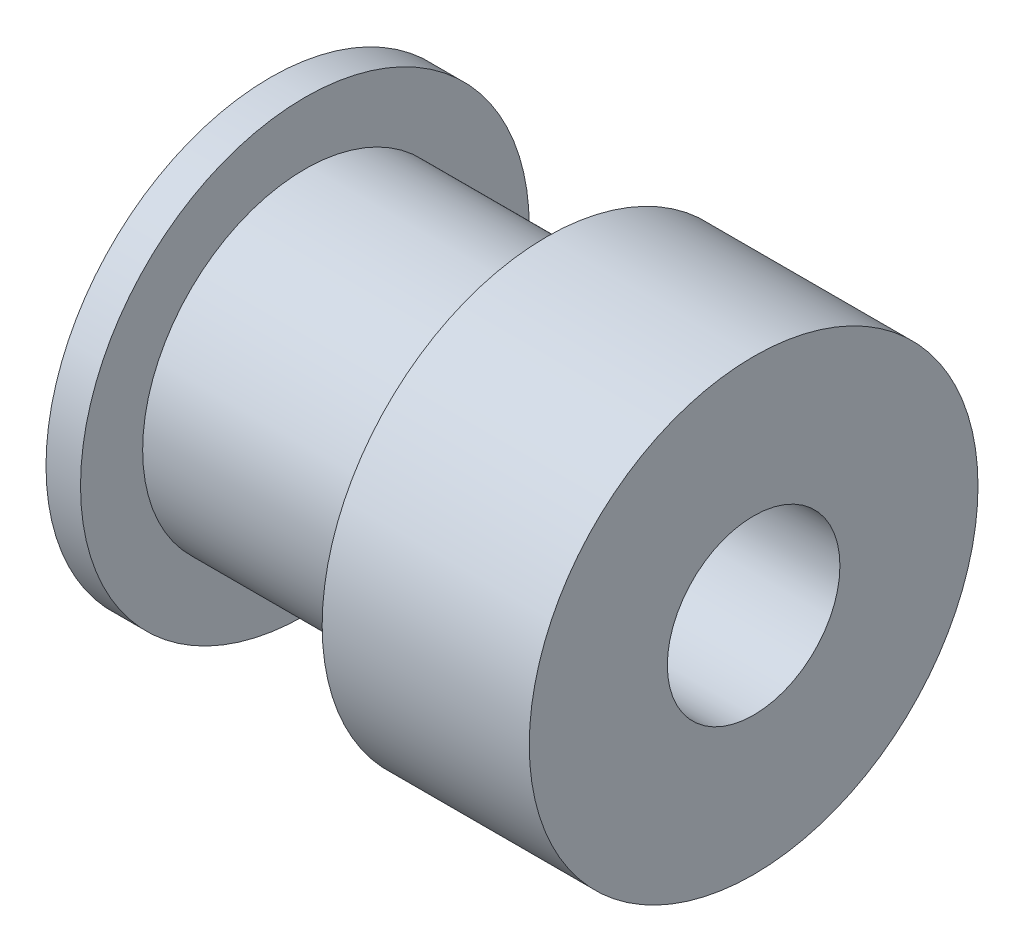
SolidWorks part; units mm, degrees
ref_plane "Front Plane" through (0, 0, 0) normal (0, 0, 1) x (1, 0, 0)
ref_plane "Top Plane" through (0, 0, 0) normal (0, 1, 0) x (1, 0, 0)
ref_plane "Right Plane" through (0, 0, 0) normal (1, 0, 0) x (0, 0, -1)
sketch "Sketch1" plane through (0, 0, 0) normal (0, 0, 1) x (1, 0, 0)
  line L0 (0, 0) -> (20.2857, 0) construction
  line L1 (0, -2.5) -> (0, -6.5)
  line L2 (0, -6.5) -> (1, -6.5)
  line L3 (1, -6.5) -> (1, -4.7)
  line L4 (1, -4.7) -> (8, -4.7)
  line L5 (8, -4.7) -> (8, -6.5)
  line L6 (8, -6.5) -> (14, -6.5)
  line L7 (14, -2.5) -> (14, -6.5)
  line L8 (0, -2.5) -> (14, -2.5)
  dimension "D1" = 14
  dimension "D5" = 4.7
  dimension "D6" = 2.5
  dimension "D4" = 6.5
  dimension "D2" = 1
  dimension "D3" = 7
revolve "Revolve1" add sketch "Sketch1" angle 360 about L0
equation "\"height\"=14"
equation "\"D1@Sketch1\"=\"height\""
equation "\"bore\"= 5"
equation "\"D6@Sketch1\"= \"bore\" / 2"
equation "\"OD\"= 13"
equation "\"D4@Sketch1\"= \"OD\" / 2"
equation "\"small lip\"=1"
equation "\"D2@Sketch1\"=\"small lip\""
equation "\"geared section\"=7"
equation "\"D3@Sketch1\"=\"geared section\""
equation "\"gear OD\"= 9.4"
equation "\"D5@Sketch1\"= \"gear OD\" / 2"
